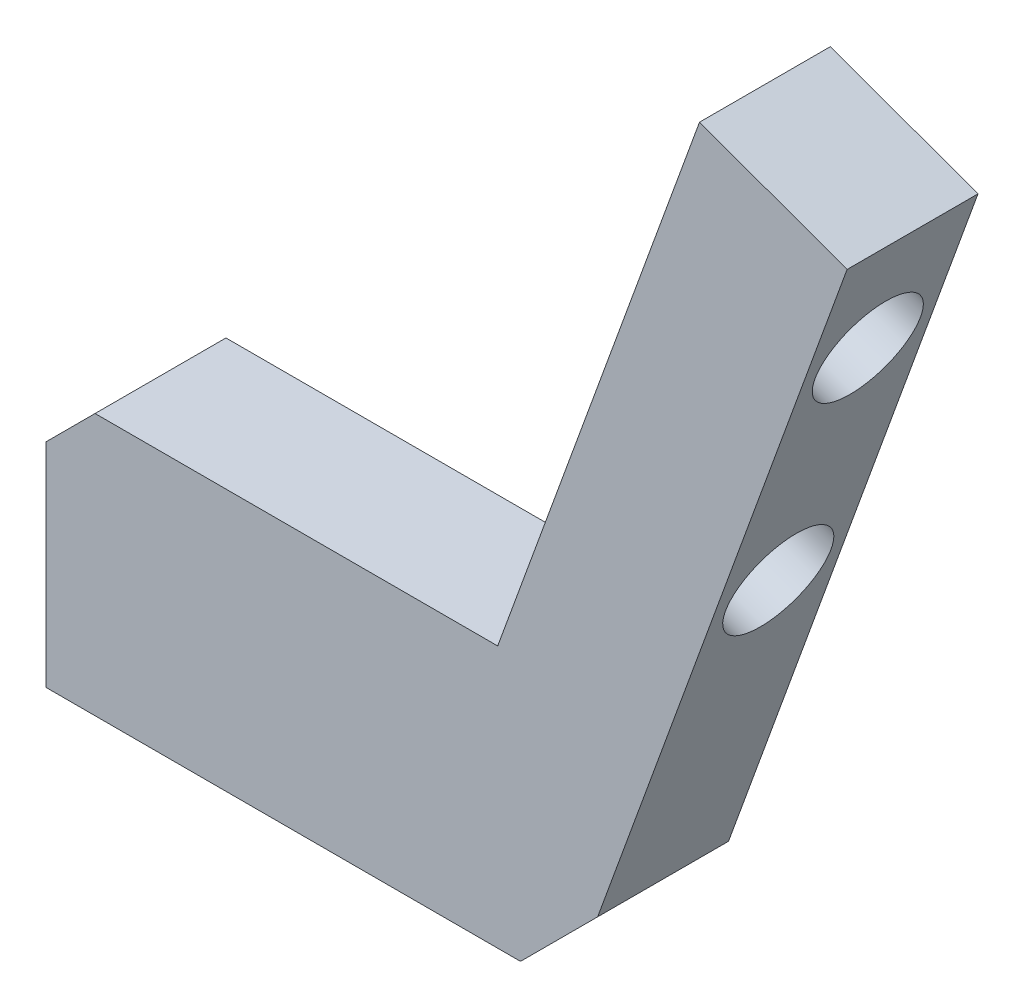
SolidWorks part; units mm, degrees
ref_plane "Front Plane" through (0, 0, 0) normal (0, 0, 1) x (1, 0, 0)
ref_plane "Top Plane" through (0, 0, 0) normal (0, 1, 0) x (1, 0, 0)
ref_plane "Right Plane" through (0, 0, 0) normal (1, 0, 0) x (0, 0, -1)
sketch "Sketch1" plane through (0, 0, 0) normal (0, 0, 1) x (1, 0, 0)
  line L0 (-25.4, 0) -> (0, 0)
  line L1 (0, 0) -> (13.4653, 36.9957)
  line L4 (-25.4, 12.7) -> (-25.4, 0)
  line L5 (13.4653, 36.9957) -> (6.3049, 39.6019)
  line L6 (6.3049, 39.6019) -> (-3.4866, 12.7)
  line L9 (-25.4, 12.7) -> (-3.4866, 12.7)
  dimension "D1" = 70
  dimension "D2" = 12.7
  dimension "D3" = 25.4
  dimension "D4" = 7.62
  dimension "D5" = 39.37
extrude "Boss-Extrude1" add sketch "Sketch1" along normal mid plane 6.35
sketch "Sketch2" plane through (0, 0, 0) normal (0, -1, 0) x (1, 0, 0)
  line L0 (-25.4, 0) -> (-22.225, 0) construction
  line L1 (-25.4, 3.175) -> (-25.4, -3.175) construction
  line L2 (-22.225, 0) -> (-9.525, 0) construction
  point P1 (-10.5609, 0)
  point P3 (-22.225, 0)
  point P4 (-9.525, 0)
  dimension "D2" = 3.175
  dimension "D1" = 12.7
hole_wizard "Tap Drill for #10-24 Tap1" positions "Sketch3" profile "Sketch4" hole size "#10-24" standard "ANSI Inch"
sketch "Sketch3" plane through (0, 0, 0) normal (0, -1, 0) x (-1, 0, 0)
  point P0 (22.225, 0)
  point P3 (9.525, 0)
sketch "Sketch4" plane through (-22.225, 0, 0) normal (1, 0, 0) x (0, 0, -1)
  line L0 (0, 0) -> (0, 11.3008)
  line L1 (0, 11.3008) -> (1.8986, 10.16)
  line L2 (1.8986, 10.16) -> (1.8986, 0)
  line L5 (1.8986, 0) -> (0, 0)
  line L10 (0, 11.3008) -> (-1.8987, 10.16) construction
  line L11 (0, -6.35) -> (0, 107.95) construction
  dimension "Hole Dia." = 3.7973
  dimension "Hole Depth" = 10.16
  dimension "Drill Angle" = 118
ref_plane "Plane1" through (0, 0, 0) normal (-0.8192, -0.5736, 0) x (0, 0, 1)
chamfer "Chamfer1" distance 2.38 angle 45 2 edges at (0, 0, 0) (-25.4, 12.7, 0)
sketch "Sketch5" plane through (0, 0, 0) normal (0.9397, -0.342, 0) x (0, 0, -1)
  line L0 (0, 39.37) -> (0, 33.02) construction
  line L1 (-3.175, 39.37) -> (3.175, 39.37) construction
  line L2 (0, 33.02) -> (0, 20.32) construction
  point P6 (0, 22.23)
  point P7 (0, 20.32)
  point P8 (0, 33.02)
  dimension "D1" = 6.35
  dimension "D2" = 12.7
hole_wizard "#10 Clearance Hole1" positions "Sketch6" profile "Sketch7" hole size "#10" standard "ANSI Inch"
sketch "Sketch6" plane through (0, 0, 0) normal (0.9397, -0.342, 0) x (0, 0, -1)
  point P0 (0, 33.02)
  point P3 (0, 20.32)
sketch "Sketch7" plane through (11.2935, 31.0287, 0) normal (0, 0, 1) x (0.342, 0.9397, 0)
  line L0 (0, 0) -> (0, 14.2338)
  line L1 (0, 14.2338) -> (2.5527, 12.7)
  line L2 (2.5527, 12.7) -> (2.5527, 0)
  line L5 (2.5527, 0) -> (0, 0)
  line L10 (0, 14.2338) -> (-2.5527, 12.7) construction
  line L11 (0, -6.35) -> (0, 107.95) construction
  dimension "Hole Dia." = 5.1054
  dimension "Hole Depth" = 12.7
  dimension "Drill Angle" = 118
